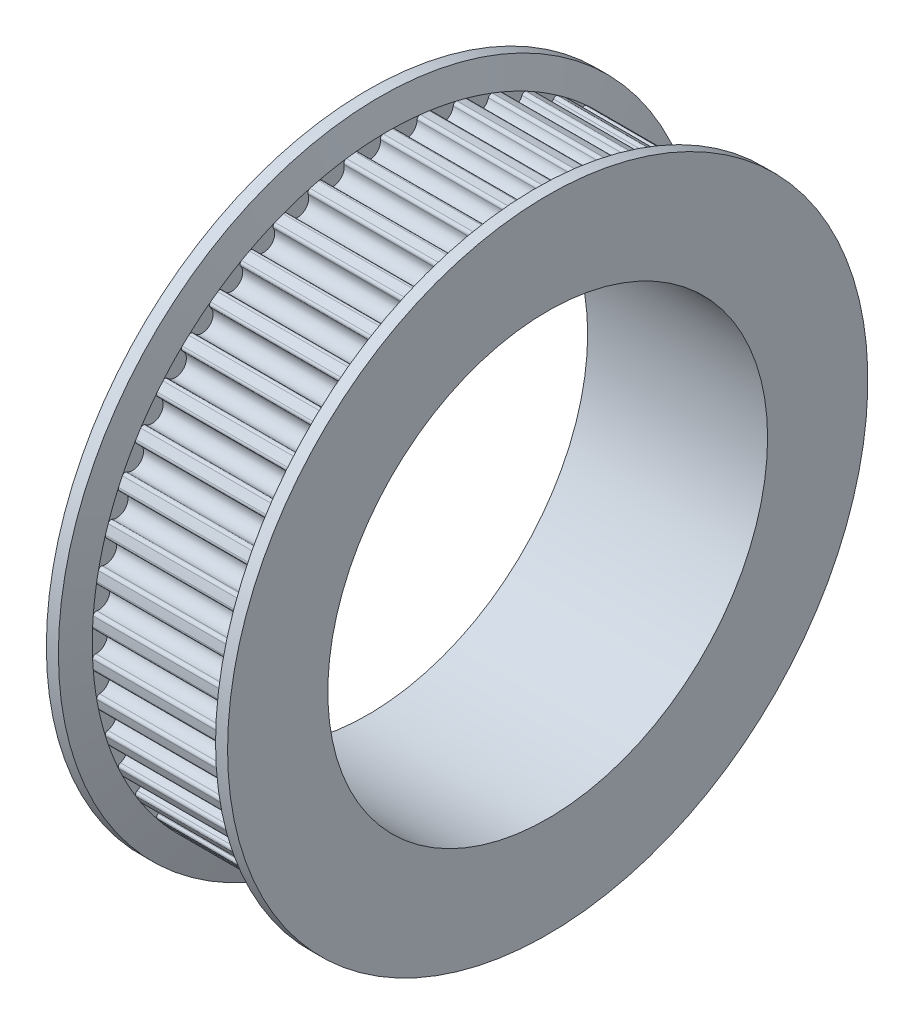
SolidWorks part; units mm, degrees
material "6061-O (SS)"
ref_plane "Сверху" through (0, 0, 0) normal (0, 0, 1) x (1, 0, 0)
ref_plane "Справа" through (0, 0, 0) normal (0, 1, 0) x (1, 0, 0)
ref_plane "Спереди" through (0, 0, 0) normal (1, 0, 0) x (0, 0, -1)
sketch "bod" plane through (0, 0, 0) normal (0, 0, 1) x (1, 0, 0)
  line L3 (14.9588, 12.5217) -> (5.3685, 12.5217) construction
  line L4 (7, 14.78) -> (14, 14.78)
  line L5 (6, 0) -> (6, 12.4805)
  line L6 (14.3982, 16.0142) -> (15, 16.0142)
  line L7 (15, 0) -> (15, 12.4805)
  line L8 (15, 12.4805) -> (14.9588, 12.5217)
  line L9 (14.9588, 12.5217) -> (15, 12.5629)
  line L10 (15, 12.5629) -> (15, 16.0142)
  line L11 (6, 0) -> (15, 0)
  line L12 (6, 16.0796) -> (6.6018, 16.0796)
  line L13 (14, 14.78) -> (14.3982, 16.0142)
  line L14 (6.6018, 16.0796) -> (7, 14.78)
  line L15 (6, 12.4805) -> (6.0412, 12.5217)
  line L16 (6.0412, 12.5217) -> (6, 12.5629)
  line L17 (6, 12.5629) -> (6, 16.0796)
  dimension "D1" = 1
  dimension "D5" = 1
  dimension "D6" = 14.78
  dimension "D8" = 7
revolve "Body" add sketch "bod" angle 360 about L11
sketch "tooth" plane through (6, 0, 0) normal (-1, 0, 0) x (0, 0, 1)
  line L0 (0, 0) -> (9.7637, 0) construction
  circle A0 centre (14.4574, -1.8264) radius 0.55
  circle A1 centre (-11.7892, -8.5654) radius 0.55
  circle A2 centre (14.1144, -3.624) radius 0.55
  circle A3 centre (13.5489, -5.3644) radius 0.55
  circle A4 centre (12.7698, -7.0202) radius 0.55
  circle A5 centre (11.7892, -8.5654) radius 0.55
  circle A6 centre (14.5723, 0) radius 0.55
  circle A7 centre (10.6227, -9.9754) radius 0.55
  circle A8 centre (9.2887, -11.2281) radius 0.55
  circle A9 centre (7.8082, -12.3038) radius 0.55
  circle A10 centre (6.2046, -13.1854) radius 0.55
  circle A11 centre (4.5031, -13.859) radius 0.55
  circle A12 centre (2.7306, -14.3141) radius 0.55
  circle A13 centre (0.915, -14.5435) radius 0.55
  circle A14 centre (-0.915, -14.5435) radius 0.55
  circle A15 centre (-12.7698, -7.0202) radius 0.55
  circle A16 centre (-13.5489, -5.3644) radius 0.55
  circle A17 centre (-2.7306, -14.3141) radius 0.55
  circle A18 centre (-4.5031, -13.859) radius 0.55
  circle A19 centre (-6.2046, -13.1854) radius 0.55
  circle A20 centre (-7.8082, -12.3038) radius 0.55
  circle A21 centre (-9.2887, -11.2281) radius 0.55
  circle A22 centre (-10.6227, -9.9754) radius 0.55
  circle A23 centre (-14.1144, -3.624) radius 0.55
  circle A24 centre (-14.4574, -1.8264) radius 0.55
  circle A25 centre (-14.5723, 0) radius 0.55
  circle A26 centre (-14.4574, 1.8264) radius 0.55
  circle A27 centre (-14.1144, 3.624) radius 0.55
  circle A28 centre (-13.5489, 5.3644) radius 0.55
  circle A29 centre (-12.7698, 7.0202) radius 0.55
  circle A30 centre (-11.7892, 8.5654) radius 0.55
  circle A31 centre (-10.6227, 9.9754) radius 0.55
  circle A32 centre (-9.2887, 11.2281) radius 0.55
  circle A33 centre (-7.8082, 12.3038) radius 0.55
  circle A34 centre (-6.2046, 13.1854) radius 0.55
  circle A35 centre (-4.5031, 13.859) radius 0.55
  circle A36 centre (-2.7306, 14.3141) radius 0.55
  circle A37 centre (-0.915, 14.5435) radius 0.55
  circle A38 centre (0.915, 14.5435) radius 0.55
  circle A39 centre (2.7306, 14.3141) radius 0.55
  circle A40 centre (4.5031, 13.859) radius 0.55
  circle A41 centre (6.2046, 13.1854) radius 0.55
  circle A42 centre (7.8082, 12.3038) radius 0.55
  circle A43 centre (9.2887, 11.2281) radius 0.55
  circle A44 centre (10.6227, 9.9754) radius 0.55
  circle A45 centre (11.7892, 8.5654) radius 0.55
  circle A46 centre (12.7698, 7.0202) radius 0.55
  circle A47 centre (13.5489, 5.3644) radius 0.55
  circle A48 centre (14.1144, 3.624) radius 0.55
  circle A49 centre (14.4574, 1.8264) radius 0.55
  point P45 (0, 0)
  dimension "D1" = 50
  dimension "D2" = 1.83
extrude "20tooth" cut sketch "tooth" against normal blind 7 from offset 1 offset against normal yes
fillet "chfr" radius 0.15 100 edges at (10.5, 0.5128, 14.7711) (10.5, -0.5128, 14.7711) (10.5, -1.3426, 14.7189) (10.5, -2.3601, 14.5904) (10.5, -3.1767, 14.4346) (10.5, -4.1701, 14.1795) (10.5, -4.9608, 13.9226) (10.5, -5.9144, 13.545) (10.5, -6.6667, 13.1911) (10.5, -7.5654, 12.697) (10.5, -8.2674, 12.2515) (10.5, -9.0971, 11.6487) (10.5, -9.7377, 11.1187) (10.5, -10.4853, 10.4166) (10.5, -11.0545, 9.8106) (10.5, -11.7082, 9.0203) (10.5, -12.1969, 8.3477) (10.5, -12.7464, 7.4818) (10.5, -13.147, 6.7532) (10.5, -13.5836, 5.8252) (10.5, -13.8897, 5.0522) (10.5, -14.2066, 4.0768) (10.5, -14.4134, 3.2715) (10.5, -14.6056, 2.2641) (10.5, -14.7098, 1.4393) (10.5, -14.7742, 0.4157) (10.5, -14.7742, -0.4157) (10.5, -14.7098, -1.4393) (10.5, -14.6056, -2.2641) (10.5, -14.4134, -3.2715) (10.5, -14.2066, -4.0768) (10.5, -13.8897, -5.0522) (10.5, -13.5836, -5.8252) (10.5, -13.147, -6.7532) (10.5, -12.7464, -7.4818) (10.5, -12.1969, -8.3477) (10.5, -11.7082, -9.0203) (10.5, -11.0545, -9.8106) (10.5, -10.4853, -10.4166) (10.5, -9.7377, -11.1187) (10.5, -4.1701, -14.1795) (10.5, -3.1767, -14.4346) (10.5, -5.9144, -13.545) (10.5, -4.9608, -13.9226) (10.5, -7.5654, -12.697) (10.5, -6.6667, -13.1911) (10.5, -9.0971, -11.6487) (10.5, -8.2674, -12.2515) (10.5, -2.3601, -14.5904) (10.5, -1.3426, -14.7189) (10.5, -0.5128, -14.7711) (10.5, 0.5128, -14.7711) (10.5, 1.3426, -14.7189) (10.5, 2.3601, -14.5904) (10.5, 3.1767, -14.4346) (10.5, 4.1701, -14.1795) (10.5, 4.9608, -13.9226) (10.5, 5.9144, -13.545) (10.5, 6.6667, -13.1911) (10.5, 7.5654, -12.697) (10.5, 8.2674, -12.2515) (10.5, 9.0971, -11.6487) (10.5, 9.7377, -11.1187) (10.5, 10.4853, -10.4166) (10.5, 11.0545, -9.8106) (10.5, 11.7082, -9.0203) (10.5, 12.1969, -8.3477) (10.5, 12.7464, -7.4818) (10.5, 13.147, -6.7532) (10.5, 13.5836, -5.8252) (10.5, 13.8897, -5.0522) (10.5, 14.2066, -4.0768) (10.5, 14.4134, -3.2715) (10.5, 14.6056, -2.2641) (10.5, 14.7098, -1.4393) (10.5, 14.7742, -0.4157) (10.5, 14.7742, 0.4157) (10.5, 14.7098, 1.4393) (10.5, 14.6056, 2.2641) (10.5, 14.4134, 3.2715) (10.5, 14.2066, 4.0768) (10.5, 13.8897, 5.0522) (10.5, 13.5836, 5.8252) (10.5, 13.147, 6.7532) (10.5, 12.7464, 7.4818) (10.5, 12.1969, 8.3477) (10.5, 11.7082, 9.0203) (10.5, 11.0545, 9.8106) (10.5, 10.4853, 10.4166) (10.5, 9.7377, 11.1187) (10.5, 9.0971, 11.6487) (10.5, 8.2674, 12.2515) (10.5, 7.5654, 12.697) (10.5, 6.6667, 13.1911) (10.5, 5.9144, 13.545) (10.5, 4.9608, 13.9226) (10.5, 4.1701, 14.1795) (10.5, 3.1767, 14.4346) (10.5, 2.3601, 14.5904) (10.5, 1.3426, 14.7189)
sketch "Sketch1" plane through (15, 0, 0) normal (1, 0, 0) x (0, 0, -1)
  circle A0 centre (0, 0) radius 11
  circle A1 centre (0, 0) radius 12.5629
  dimension "D1" = 22
extrude "Boss-Extrude1" add sketch "Sketch1" against normal blind 9
